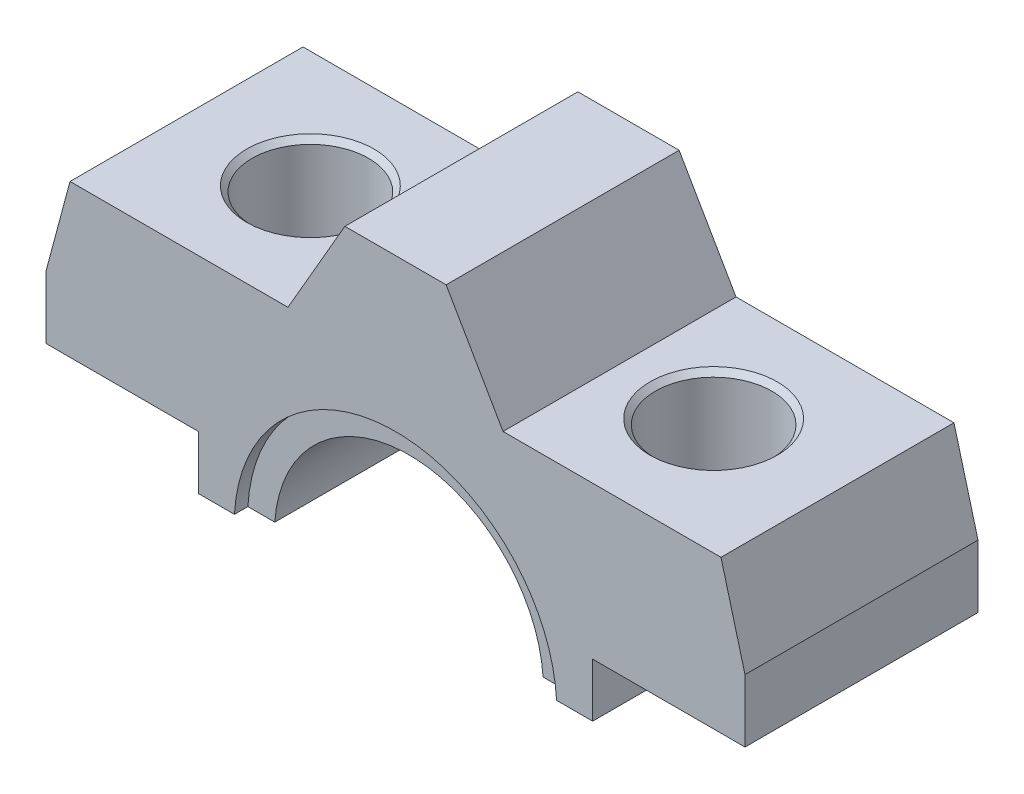
SolidWorks part; units mm, degrees
material "Простая углеродистая сталь"
ref_plane "Спереди" through (0, 0, 0) normal (0, 0, 1) x (1, 0, 0)
ref_plane "Сверху" through (0, 0, 0) normal (0, 1, 0) x (1, 0, 0)
ref_plane "Справа" through (0, 0, 0) normal (1, 0, 0) x (0, 0, -1)
sketch "Эскиз1" plane through (0, 0, 0) normal (0, 0, 1) x (1, 0, 0)
  line L0 (-75.5144, 7) -> (79.0283, 7) construction
  line L1 (0, -29.7379) -> (0, 81.53) construction
  line L2 (-35.0999, 24) -> (-12, 24)
  line L3 (-12, 24) -> (-5.6491, 35)
  line L4 (-5.6491, 35) -> (5.6491, 35)
  line L5 (5.6491, 35) -> (12, 24)
  line L6 (12, 24) -> (35.0999, 24)
  line L7 (-39, 7) -> (-22, 7)
  line L8 (-22, 7) -> (-22, 1)
  line L9 (-22, 0) -> (22, 0) construction
  line L10 (-22, 1) -> (22, 1)
  line L11 (22, 1) -> (22, 7)
  line L12 (22, 7) -> (39, 7)
  line L13 (12, 24) -> (12, 27.3464) construction
  arc A0 (39, 7) -> (35.0999, 24) centre (0, 7) ccw
  arc A2 (-35.0999, 24) -> (-39, 7) centre (0, 7) ccw
  dimension "D1" = 44
  dimension "D2" = 39
  dimension "D4" = 1
  dimension "D3" = 7
  dimension "D5" = 24
  dimension "D6" = 24
  dimension "D7" = 30
  dimension "D8" = 35
extrude "Бобышка-Вытянуть1" add sketch "Эскиз1" against normal blind 26
sketch "Эскиз2" plane through (0, 0, 0) normal (0, 0, 1) x (1, 0, 0)
  line L0 (-22, 0) -> (22, 0) construction
  line L1 (-22, 0) -> (22, 0) construction
  line L2 (0, -29.7379) -> (0, 81.53) construction
  line L3 (0, -29.7379) -> (0, 81.53) construction
  circle A0 centre (0, 0) radius 15
  dimension "D1" = 30
extrude "Вырез-Вытянуть1" cut sketch "Эскиз2" against normal through all
sketch "Эскиз3" plane through (0, 0, 0) normal (0, 0, 1) x (1, 0, 0)
  line L0 (-22, 0) -> (22, 0) construction
  line L1 (0, -29.7379) -> (0, 81.53) construction
  line L2 (-22, 0) -> (22, 0) construction
  line L3 (0, -29.7379) -> (0, 81.53) construction
  circle A0 centre (0, 0) radius 18
  dimension "D1" = 36
extrude "Вырез-Вытянуть2" cut sketch "Эскиз3" against normal blind 1.5
sketch "Эскиз4" plane through (0, 0, -26) normal (0, 0, -1) x (-1, 0, 0)
  line L0 (22, 0) -> (-22, 0) construction
  line L1 (0, -29.7379) -> (0, 81.53) construction
  line L2 (22, 0) -> (-22, 0) construction
  line L3 (0, -29.7379) -> (0, 81.53) construction
  circle A0 centre (0, 0) radius 18
  dimension "D1" = 36
extrude "Вырез-Вытянуть3" cut sketch "Эскиз4" against normal blind 1.5
sketch "Эскиз9" plane through (0, 0, 0) normal (0, 0, 1) x (1, 0, 0)
  line L6 (-39, 7) -> (-39, 14)
  line L7 (39, 7) -> (39, 14)
  line L8 (-39, 14) -> (-36.3205, 24)
  line L9 (39, 14) -> (36.3205, 24)
  line L10 (-22, 7) -> (-22, 24)
  line L11 (22, 7) -> (22, 24)
  line L15 (22, 1) -> (22, 7)
  line L16 (22, 7) -> (39, 7)
  line L17 (35.0999, 24) -> (12, 24)
  line L18 (12, 24) -> (5.6491, 35)
  line L19 (5.6491, 35) -> (-5.6491, 35)
  line L20 (-5.6491, 35) -> (-12, 24)
  line L21 (-12, 24) -> (-35.0999, 24)
  line L22 (-39, 7) -> (-22, 7)
  line L23 (-22, 7) -> (-22, 1)
  line L24 (-22, 1) -> (22, 1)
  line L26 (22, 7) -> (39, 7)
  line L27 (36.3205, 24) -> (22, 24)
  line L31 (-22, 24) -> (-36.3205, 24)
  line L32 (-39, 7) -> (-22, 7)
  arc A2 (39, 7) -> (35.0999, 24) centre (0, 7) ccw
  arc A3 (-35.0999, 24) -> (-39, 7) centre (0, 7) ccw
  dimension "D2" = 10
  dimension "D3" = 15
  dimension "D4" = 10
  dimension "D5" = 15
  dimension "D6" = 78
  dimension "D1" = 0
extrude "Бобышка-Вытянуть2" add sketch "Эскиз9" against normal up to surface (26 mm away) up to face at (0, 15.3887, -26)
sketch "Эскиз6" plane through (0, 24, 0) normal (0, 1, 0) x (1, 0, 0)
  line L0 (-46.5747, 13) -> (44.1615, 13) construction
  line L1 (0, -15.7573) -> (0, 36.046) construction
  circle A0 centre (-22.5, 13) radius 6.5
  circle A1 centre (22.5, 13) radius 6.5
  dimension "D4" = 13
  dimension "D5" = 13
  dimension "D1" = 13
  dimension "D2" = 45
  dimension "D3" = 22.5
extrude "Вырез-Вытянуть5" cut sketch "Эскиз6" against normal through all
chamfer "Фаска1" distance 0.6 angle 45 2 edges at (22.5, 24, -6.5) (-22.5, 24, -6.5)
